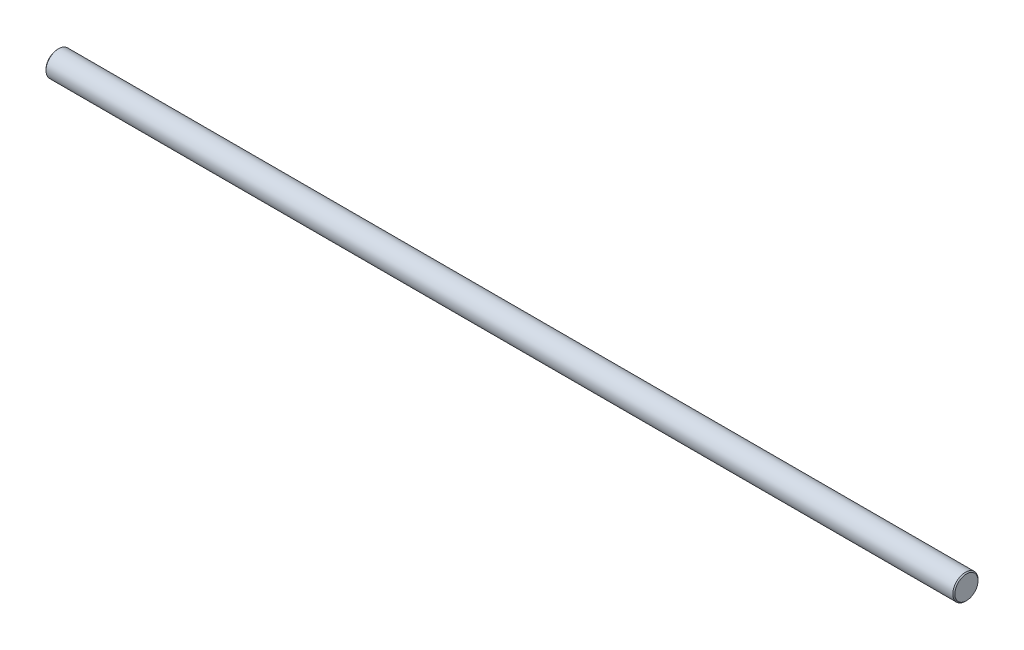
SolidWorks part; units mm, degrees
material "Alloy Steel"
ref_plane "Front Plane" through (0, 0, 0) normal (0, 0, 1) x (1, 0, 0)
ref_plane "Top Plane" through (0, 0, 0) normal (0, 1, 0) x (1, 0, 0)
ref_plane "Right Plane" through (0, 0, 0) normal (1, 0, 0) x (0, 0, -1)
sketch "Sketch1" plane through (0, 0, 0) normal (1, 0, 0) x (0, 0, -1)
  circle A0 centre (0, 0) radius 6.3437
  dimension "D1" = 12.6873
extrude "Boss-Extrude1" add sketch "Sketch1" along normal mid plane 457.2 contours A0
chamfer "Chamfer1" distance 0.508 angle 45 2 edges at (-228.6, 0, -6.3437) (228.6, 0, -6.3437)
